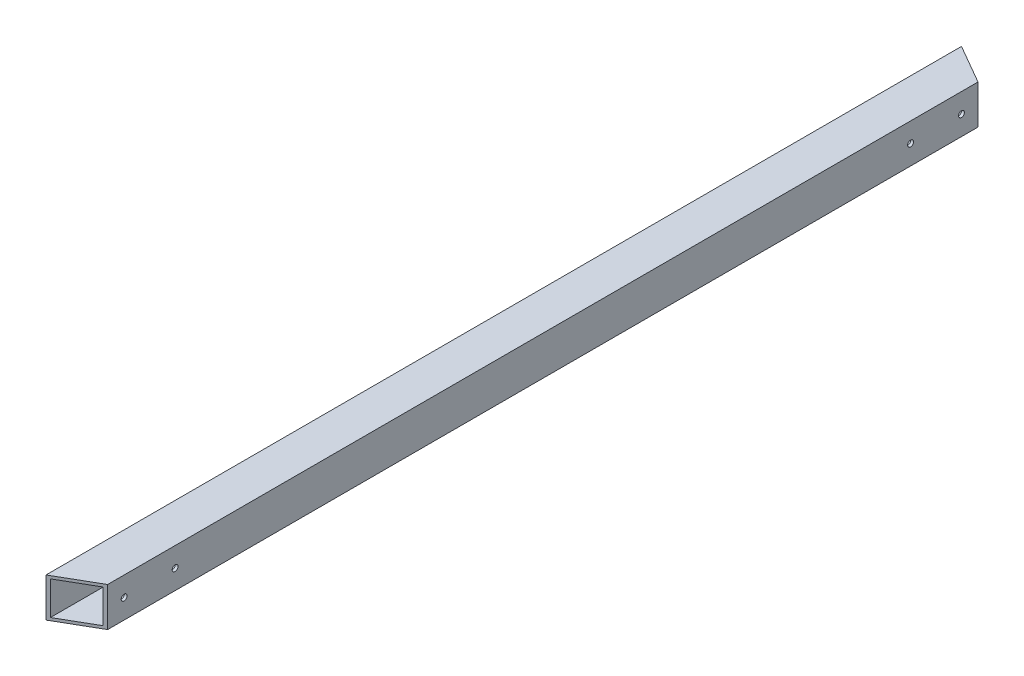
SolidWorks part; units mm, degrees
material "6061 Alloy"
ref_plane "Front Plane" through (0, 0, 0) normal (0, 0, 1) x (1, 0, 0)
ref_plane "Top Plane" through (0, 0, 0) normal (0, 1, 0) x (1, 0, 0)
ref_plane "Right Plane" through (0, 0, 0) normal (1, 0, 0) x (0, 0, -1)
sketch "Sketch1" plane through (0, 0, 0) normal (0, 0, 1) x (1, 0, 0)
  line L1 (-22.225, 22.225) -> (22.225, 22.225)
  line L2 (-22.225, 22.225) -> (-22.225, -22.225)
  line L3 (-22.225, -22.225) -> (22.225, -22.225)
  line L4 (22.225, 22.225) -> (22.225, -22.225)
  line L5 (-22.225, 22.225) -> (22.225, -22.225) construction
  line L6 (-22.225, -22.225) -> (22.225, 22.225) construction
  line L7 (-19.05, 19.05) -> (19.05, 19.05)
  line L8 (-19.05, 19.05) -> (-19.05, -19.05)
  line L9 (-19.05, -19.05) -> (19.05, -19.05)
  line L10 (19.05, 19.05) -> (19.05, -19.05)
  line L11 (-19.05, 19.05) -> (19.05, -19.05) construction
  line L12 (-19.05, -19.05) -> (19.05, 19.05) construction
  point P0 (0, 0)
  point P6 (0, 0)
  dimension "D1" = 44.45
  dimension "D2" = 44.45
  dimension "D3" = 3.175
extrude "Boss-Extrude1" add sketch "Sketch1" along normal blind 1041.4
sketch "Sketch2" plane through (0, 22.225, 0) normal (0, 1, 0) x (1, 0, 0)
  line L0 (-22.225, -1041.4) -> (22.225, -1041.4)
  line L1 (22.225, -1041.4) -> (22.225, -1015.7368)
  line L2 (22.225, -1041.4) -> (22.225, 0) construction
  line L3 (22.225, -1015.7368) -> (-22.225, -1041.4)
  line L6 (-22.225, -1041.4) -> (-22.225, 0) construction
  line L9 (-22.225, 0) -> (22.225, -25.6632)
  line L10 (22.225, -25.6632) -> (22.225, 0)
  line L11 (22.225, 0) -> (-22.225, 0)
  dimension "D1" = 60
  dimension "D2" = 60
extrude "Cut-Extrude2" cut sketch "Sketch2" against normal blind 1041.4
sketch "Sketch9" plane through (-22.225, 0, 0) normal (-1, 0, 0) x (0, 0, 1)
  line L0 (1041.4, -22.225) -> (0, -22.225) construction
  line L1 (0, 22.225) -> (0, -22.225) construction
  line L2 (1041.4, 22.225) -> (1041.4, -22.225) construction
  circle A0 centre (996.95, 0) radius 3.3734
  circle A1 centre (44.45, 0) radius 3.3734
  circle A2 centre (102.3897, 0) radius 3.3734
  circle A3 centre (939.0103, 0) radius 3.3734
  dimension "D1" = 6.7469
  dimension "D2" = 6.7469
  dimension "D3" = 6.7469
  dimension "D4" = 6.7469
  dimension "D5" = 57.9397
  dimension "D6" = 57.9397
  dimension "D7" = 22.225
  dimension "D8" = 44.45
  dimension "D9" = 22.225
  dimension "D10" = 22.225
  dimension "D11" = 22.225
  dimension "D12" = 44.45
extrude "Cut-Extrude3" cut sketch "Sketch9" against normal through all
